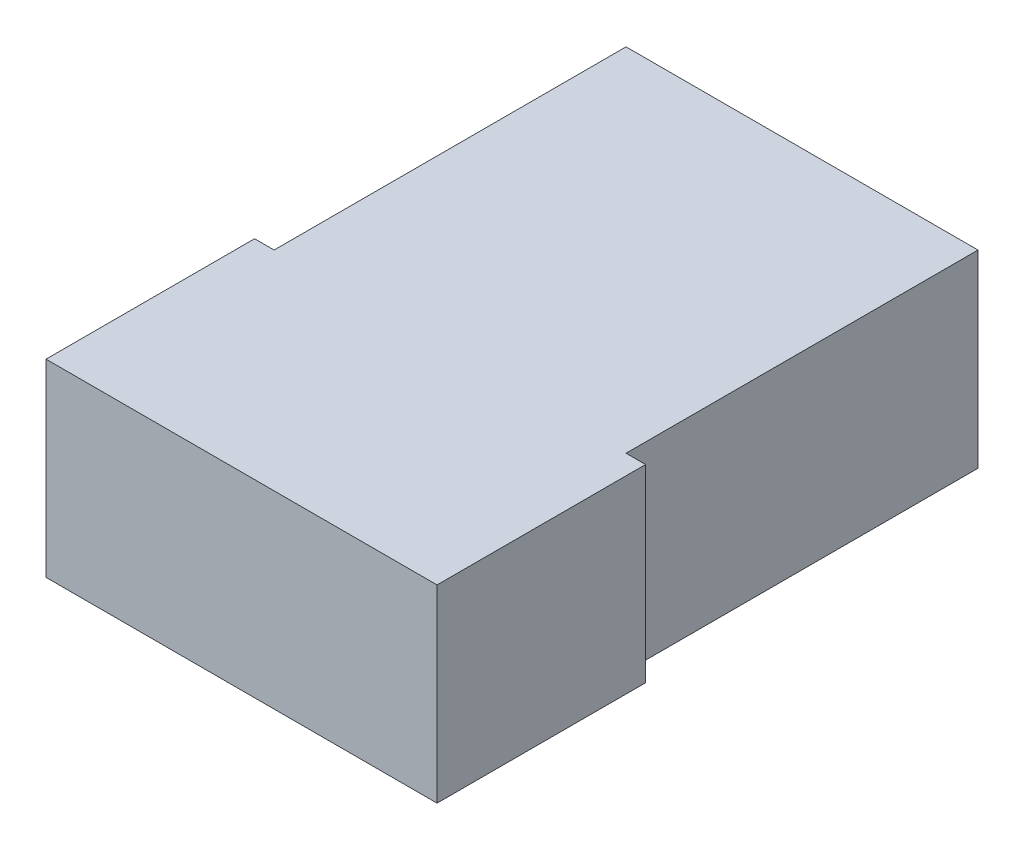
SolidWorks part; units mm, degrees
material "PETG"
ref_plane "Front Plane" through (0, 0, 0) normal (0, 0, 1) x (1, 0, 0)
ref_plane "Top Plane" through (0, 0, 0) normal (0, 1, 0) x (1, 0, 0)
ref_plane "Right Plane" through (0, 0, 0) normal (1, 0, 0) x (0, 0, -1)
other "Configuration Table"
sketch "Sketch1" plane through (0, 0, 0) normal (0, 1, 0) x (1, 0, 0)
  line L1 (-13.5, -13.5) -> (13.5, -13.5)
  line L2 (-13.5, -13.5) -> (-13.5, 13.5)
  line L3 (-13.5, 13.5) -> (13.5, 13.5)
  line L4 (13.5, -13.5) -> (13.5, 13.5)
  line L5 (-13.5, -13.5) -> (13.5, 13.5) construction
  line L6 (-13.5, 13.5) -> (13.5, -13.5) construction
  point P6 (0, 0)
  dimension "D1" = 27
  dimension "D2" = 27
extrude "Lid_Block" add sketch "Sketch1" along normal blind 14.5 from offset 48
sketch "Sketch2" plane through (0, 0, 0) normal (0, 1, 0) x (1, 0, 0)
  line L0 (-15, -29.5) -> (15, -29.5)
  line L1 (15, -29.5) -> (15, -13.5)
  line L2 (15, -13.5) -> (-15, -13.5)
  line L3 (-15, -13.5) -> (-15, -29.5)
extrude "Magnet_Ear" add sketch "Sketch2" along normal blind 14.5 from offset 48
sketch "Sketch3" plane through (0, 0, 0) normal (0, 1, 0) x (1, 0, 0)
  line L0 (-11.7, -11.7) -> (11.7, -11.7)
  line L1 (11.7, -11.7) -> (11.7, 11.7)
  line L2 (11.7, 11.7) -> (-11.7, 11.7)
  line L3 (-11.7, 11.7) -> (-11.7, -11.7)
extrude "Skirt_Recess" cut sketch "Sketch3" along normal blind 6 from offset 48
sketch "Sketch4" plane through (0, 0, 0) normal (0, 1, 0) x (1, 0, 0)
  line L0 (-7.5, -7.5) -> (7.5, -7.5)
  line L1 (7.5, -7.5) -> (7.5, 7.5)
  line L2 (7.5, 7.5) -> (-7.5, 7.5)
  line L3 (-7.5, 7.5) -> (-7.5, -7.5)
extrude "Cuvette_Cavity" cut sketch "Sketch4" along normal blind 5.5 from offset 54
sketch "Sketch5" plane through (0, 0, 0) normal (0, 1, 0) x (1, 0, 0)
  line L1 (-13.7, -28.7) -> (13.7, -28.7)
  line L2 (-13.7, -28.7) -> (-13.7, -14.3)
  line L3 (-13.7, -14.3) -> (13.7, -14.3)
  line L4 (13.7, -28.7) -> (13.7, -14.3)
  line L5 (-13.7, -28.7) -> (13.7, -14.3) construction
  line L6 (-13.7, -14.3) -> (13.7, -28.7) construction
  point P5 (0, -21.5)
  dimension "D1" = 27.4
  dimension "D2" = 14.4
extrude "Magnet_Pocket" cut sketch "Sketch5" along normal blind 8.2 from offset 48
equation "\"Jar_OD\"= 90  'ASSUMED - Part G fallback - jar outer diameter"
equation "\"Jar_H\"= 120  'ASSUMED - Part G fallback - jar height"
equation "\"Pump_L\"= 45  'ASSUMED - Part G fallback"
equation "\"Pump_W\"= 24  'ASSUMED - Part G fallback"
equation "\"Pump_H\"= 33  'ASSUMED - Part G fallback"
equation "\"Pump_Outlet_OD\"= 7.5  'ASSUMED - Part G fallback"
equation "\"Tube_OD\"= 8  'ASSUMED - Part G fallback"
equation "\"Tube_ID\"= 6  'ASSUMED - Part G fallback"
equation "\"TDS_Body_Dia\"= 12  'ASSUMED - Part G fallback"
equation "\"TDS_Wet_Len\"= 45  'ASSUMED - Part G fallback - length in water"
equation "\"DS_Tube_Dia\"= 6  'ASSUMED - Part G fallback"
equation "\"DS_Tube_Len\"= 50  'ASSUMED - Part G fallback"
equation "\"ORP_Body_Dia\"= 12  'ASSUMED - Part G fallback"
equation "\"ORP_Body_Len\"= 150  'ASSUMED - Part G fallback"
equation "\"ORP_Cap_Dia\"= 16  'ASSUMED - Part G fallback"
equation "\"Turb_W\"= 33  'ASSUMED - Part G fallback - head width"
equation "\"Turb_D\"= 28  'ASSUMED - Part G fallback - head depth"
equation "\"Turb_H\"= 30  'ASSUMED - Part G fallback - head height"
equation "\"Turb_Slot_W\"= 10  'ASSUMED - Part G fallback - slot width"
equation "\"Flow_L\"= 62  'ASSUMED - Part G fallback YF-S201"
equation "\"Flow_W\"= 36  'ASSUMED - Part G fallback"
equation "\"Flow_H\"= 35  'ASSUMED - Part G fallback"
equation "\"Thread_G12_OD\"= 20.955  'ASSUMED - Part G fallback thread G1/2 (major diameter)"
equation "\"Valve_L\"= 75  'ASSUMED - Part G fallback"
equation "\"Valve_W\"= 45  'ASSUMED - Part G fallback"
equation "\"Valve_H\"= 60  'ASSUMED - Part G fallback"
equation "\"Tee_L\"= 40  'ASSUMED - Part G fallback - overall length"
equation "\"Tee_Branch_L\"= 25  'ASSUMED - Part G fallback"
equation "\"Tee_OD\"= 12  'ASSUMED - Part G fallback"
equation "\"Cuv_W\"= 12.5  'ASSUMED - old R3 cuvette (station suppressed in SS4)"
equation "\"Cuv_D\"= 12.5  'ASSUMED - old R3 cuvette (station suppressed in SS4)"
equation "\"Cuv_H\"= 45  'ASSUMED - old R3 cuvette (station suppressed in SS4)"
equation "\"LED_Board_L\"= 20  'ASSUMED - Part G fallback"
equation "\"LED_Board_W\"= 20  'ASSUMED - Part G fallback - LED at centre"
equation "\"GUVA_L\"= 20  'ASSUMED - Part G fallback"
equation "\"GUVA_W\"= 12  'ASSUMED - Part G fallback - sensor at centre"
equation "\"Reed_L\"= 27  'ASSUMED - Part G fallback MC-38 half"
equation "\"Reed_W\"= 14  'ASSUMED - Part G fallback"
equation "\"Reed_H\"= 8  'ASSUMED - Part G fallback"
equation "\"ESP_L\"= 51  'ASSUMED - Part G fallback"
equation "\"ESP_W\"= 28  'ASSUMED - Part G fallback"
equation "\"TFT_L\"= 58  'ASSUMED - Part G fallback - board"
equation "\"TFT_W\"= 35  'ASSUMED - Part G fallback - board"
equation "\"TFT_Win_L\"= 35  'ASSUMED - Part G fallback - visible window"
equation "\"TFT_Win_W\"= 28  'ASSUMED - Part G fallback - visible window"
equation "\"Relay_L\"= 50  'ASSUMED - Part G fallback"
equation "\"Relay_W\"= 26  'ASSUMED - Part G fallback"
equation "\"Relay_H\"= 19  'ASSUMED - Part G fallback"
equation "\"Mosfet_L\"= 34  'ASSUMED - Part G fallback"
equation "\"Mosfet_W\"= 17  'ASSUMED - Part G fallback"
equation "\"Mosfet_H\"= 12  'ASSUMED - Part G fallback"
equation "\"TDS_Board_L\"= 42  'ASSUMED - Part G fallback"
equation "\"TDS_Board_W\"= 32  'ASSUMED - Part G fallback"
equation "\"Turb_Board_L\"= 38  'ASSUMED - Part G fallback"
equation "\"Turb_Board_W\"= 28  'ASSUMED - Part G fallback"
equation "\"BNC_Thread_Dia\"= 9.5  'ASSUMED - Part G fallback"
equation "\"Plate_L\"= 420  'ASSUMED - Part G fallback"
equation "\"Plate_W\"= 297  'ASSUMED - Part G fallback"
equation "\"Plate_T\"= 6  'ASSUMED - Part G fallback"
equation "\"Probe_Clr\"= 0.3  'DESIGN VALUE - Part C rule 3 - printed probe hole = diameter + 0.3"
equation "\"Cuv_Clr\"= 0.2  'DESIGN VALUE - Part C rule 3 - cuvette pocket = size + 0.2"
equation "\"Label_H\"= 0.6  'DESIGN VALUE - Part D - raised label height"
equation "\"D1@Sketch1\" = 27.0"
equation "\"D2@Sketch1\" = 27.0"
equation "\"D1@Sketch5\" = \"Reed_L\" + 0.4"
equation "\"D2@Sketch5\" = \"Reed_W\" + 0.4"
equation "\"Booster_L\"= 150  'ASSUMED - Part G fallback - booster pump"
equation "\"Booster_W\"= 95  'ASSUMED - Part G fallback"
equation "\"Booster_H\"= 100  'ASSUMED - Part G fallback"
equation "\"PTube_OD\"= 6.35  'ASSUMED - Part G fallback - product tube 1/4 inch"
equation "\"Qz_Out\"= 12  'ASSUMED - Part G fallback - quartz channel outside square"
equation "\"Qz_Path\"= 10  'ASSUMED - Part G fallback - quartz channel inside light path"
equation "\"Qz_L\"= 40  'ASSUMED - Part G fallback - quartz channel length"
equation "\"LED860_Dia\"= 5  'ASSUMED - Part G fallback - 860 nm LED"
equation "\"BPW_L\"= 5.4  'ASSUMED - Part G fallback - BPW34"
equation "\"BPW_W\"= 4.3  'ASSUMED - Part G fallback - BPW34"
equation "\"Cart_Dia\"= 50  'ASSUMED - Part G fallback - sediment and pre-carbon cartridges"
equation "\"Cart_L\"= 255  'ASSUMED - Part G fallback"
equation "\"UF_Dia\"= 50  'ASSUMED - Part G fallback - UF cartridge"
equation "\"UF_L\"= 260  'ASSUMED - Part G fallback"
equation "\"RO_Dia\"= 62  'ASSUMED - Part G fallback - RO membrane housing"
equation "\"RO_L\"= 300  'ASSUMED - Part G fallback"
equation "\"UVC_Dia\"= 40  'ASSUMED - Part G fallback - UV-C chamber"
equation "\"UVC_L\"= 300  'ASSUMED - Part G fallback"
equation "\"Tank_W\"= 260  'ASSUMED - Part G fallback - storage tank"
equation "\"Tank_D\"= 160  'ASSUMED - Part G fallback"
equation "\"Tank_H\"= 300  'ASSUMED - Part G fallback"
equation "\"Cab_W\"= 400  'ASSUMED - Part G fallback - purifier cabinet"
equation "\"Cab_D\"= 270  'ASSUMED - Part G fallback"
equation "\"Cab_H\"= 560  'ASSUMED - Part G fallback"
equation "\"ORP_Board_L\"= 40  'ASSUMED - Part G fallback - ORP buffer board"
equation "\"ORP_Board_W\"= 30  'ASSUMED - Part G fallback"
equation "\"Opt_Board_L\"= 50  'ASSUMED - Part G fallback - optical front-end board"
equation "\"Opt_Board_W\"= 40  'ASSUMED - Part G fallback"
equation "\"Buck_L\"= 43  'ASSUMED - Part G fallback - 12 V to 5 V buck module"
equation "\"Buck_W\"= 21  'ASSUMED - Part G fallback"
equation "\"Buck_H\"= 14  'ASSUMED - Part G fallback"
equation "\"BB_L\"= 165  'ASSUMED - Part G fallback - breadboard (As_Built_R3 only)"
equation "\"BB_W\"= 55  'ASSUMED - Part G fallback"
equation "\"BB_H\"= 10  'ASSUMED - Part G fallback"
